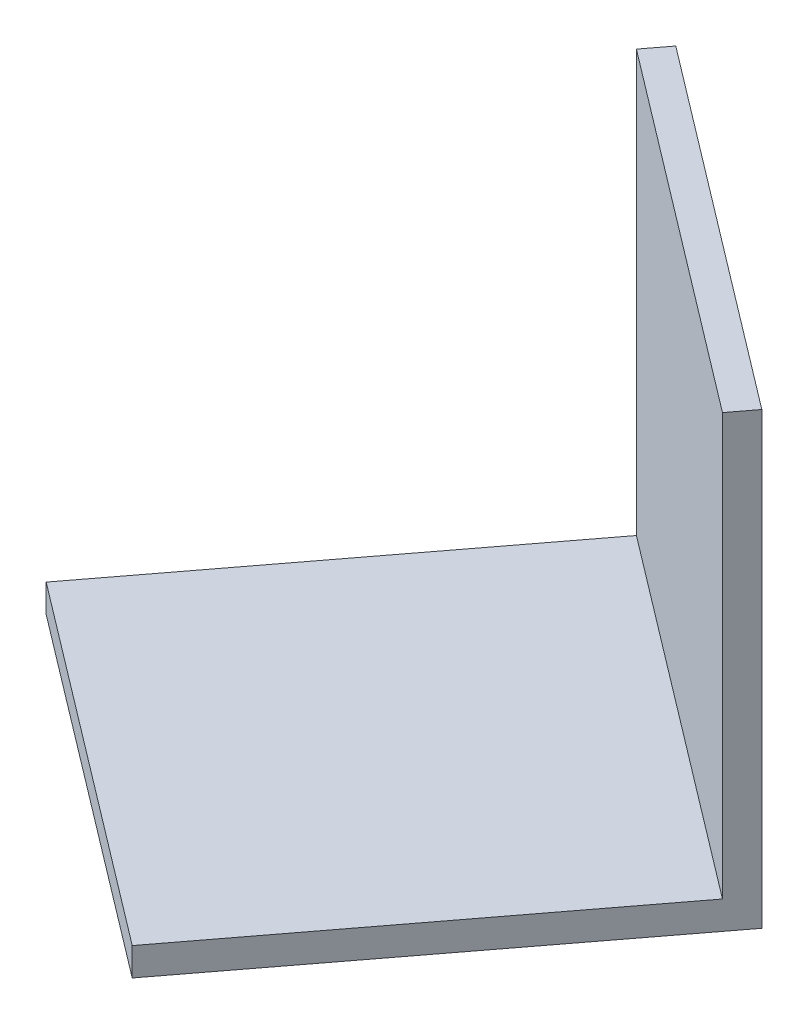
SolidWorks part; units mm, degrees
ref_plane "Front" through (0, 0, 0) normal (0, 0, 1) x (1, 0, 0)
ref_plane "Top" through (0, 0, 0) normal (0, 1, 0) x (1, 0, 0)
ref_plane "Right" through (0, 0, 0) normal (1, 0, 0) x (0, 0, -1)
sketch "Sketch1" plane through (0, 0, 0) normal (0, 1, 0) x (1, 0, 0)
  line L0 (0, 0) -> (15.3626, 20.2274)
  line L1 (0, 0) -> (-20.2274, 15.3626)
  line L2 (15.3626, 20.2274) -> (-4.8648, 35.5901)
  line L3 (-20.2274, 15.3626) -> (-4.8648, 35.5901)
  dimension "D1" = 25.4
  dimension "D2" = 25.4
extrude "Boss-Extrude1" add sketch "Sketch1" along normal blind 1.5875
sketch "Sketch2" plane through (0, 1.5875, 0) normal (0, 1, 0) x (1, 0, 0)
  line L0 (-4.8648, 35.5901) -> (-5.825, 34.3259)
  line L1 (-4.8648, 35.5901) -> (15.3626, 20.2274)
  line L2 (-5.825, 34.3259) -> (14.4025, 18.9632)
  line L3 (15.3626, 20.2274) -> (14.4025, 18.9632)
  line L4 (-4.8648, 35.5901) -> (-20.2274, 15.3626) construction
  dimension "D1" = 1.5875
  dimension "D2" = 25.4
extrude "Boss-Extrude2" add sketch "Sketch2" along normal blind 23.8125
